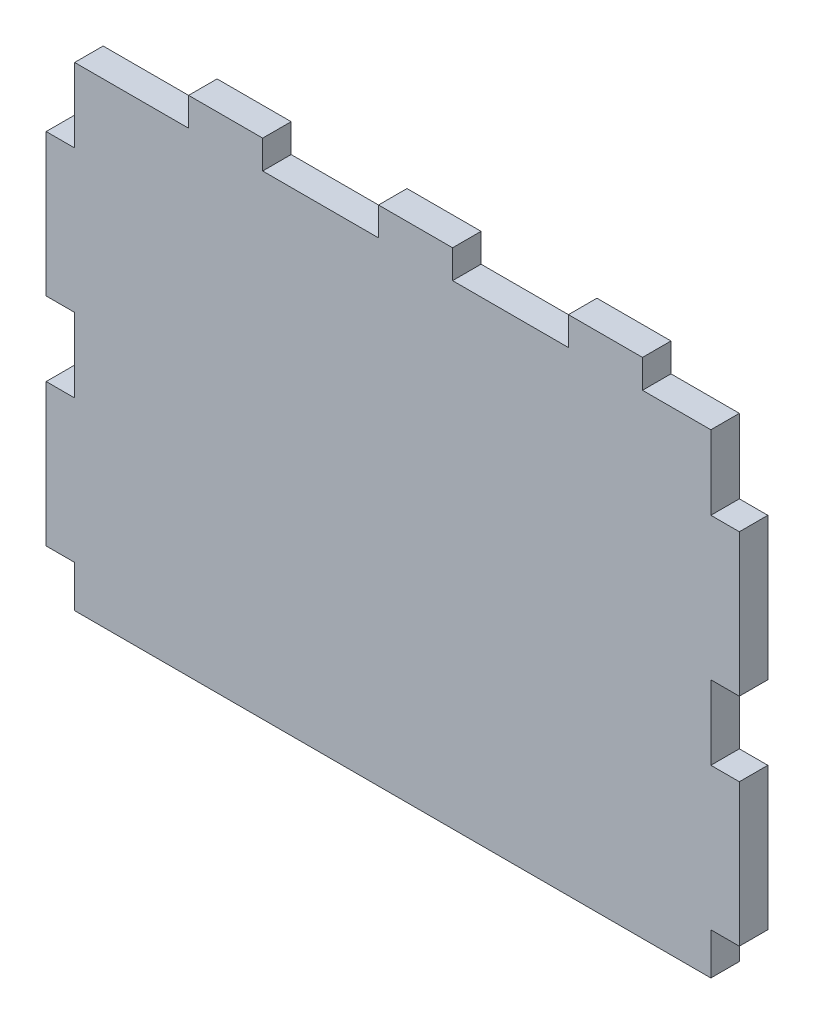
SolidWorks part; units mm, degrees
material "Oak"
ref_plane "Front Plane" through (0, 0, 0) normal (0, 0, 1) x (1, 0, 0)
ref_plane "Top Plane" through (0, 0, 0) normal (0, 1, 0) x (1, 0, 0)
ref_plane "Right Plane" through (0, 0, 0) normal (1, 0, 0) x (0, 0, -1)
sketch "Sketch1" plane through (0, 0, 0) normal (0, 0, 1) x (1, 0, 0)
  line L1 (-40.9935, 16.542) -> (32.0065, 16.542)
  line L2 (-40.9935, 16.542) -> (-40.9935, -33.458)
  line L3 (-40.9935, -33.458) -> (32.0065, -33.458)
  line L4 (32.0065, 16.542) -> (32.0065, -33.458)
  dimension "D1" = 50
  dimension "D2" = 73
extrude "Boss-Extrude1" add sketch "Sketch1" along normal blind 3
sketch "Sketch2" plane through (0, 0, 3) normal (0, 0, 1) x (1, 0, 0)
  line L12 (-40.9935, 16.542) -> (-37.9935, 16.542)
  line L13 (-40.9935, 16.542) -> (-40.9935, 8.742)
  line L14 (-40.9935, 8.742) -> (-37.9935, 8.742)
  line L15 (-37.9935, 16.542) -> (-37.9935, 8.742)
  dimension "D1" = 7.8
  dimension "D2" = 3
extrude "Cut-Extrude1" cut sketch "Sketch2" against normal through all
pattern_linear "LPattern1" count 3 spacing 22.8 along (0, -1, 0) of "Cut-Extrude1"
sketch "Sketch3" plane through (0, 0, 3) normal (0, 0, 1) x (1, 0, 0)
  line L0 (32.0065, 16.542) -> (-37.9935, 16.542) construction
  line L1 (29.0065, 16.542) -> (32.0065, 16.542)
  line L2 (29.0065, 16.542) -> (29.0065, 8.742)
  line L3 (29.0065, 8.742) -> (32.0065, 8.742)
  line L4 (32.0065, 16.542) -> (32.0065, 8.742)
  line L5 (32.0065, -33.458) -> (32.0065, 16.542) construction
  point P8 (30.5065, 16.542)
  dimension "D1" = 7.8
  dimension "D2" = 3
extrude "Cut-Extrude2" cut sketch "Sketch3" against normal through all
pattern_linear "LPattern2" count 4 spacing 22.8 along (0, -1, 0) of "Cut-Extrude2"
sketch "Sketch6" plane through (0, 0, 3) normal (0, 0, 1) x (1, 0, 0)
  line L0 (-37.9935, -33.458) -> (29.0065, -33.458) construction
  line L1 (-40.9935, -14.058) -> (-37.9935, -14.058)
  line L2 (-40.9935, -14.058) -> (-40.9935, -33.458)
  line L3 (-40.9935, -33.458) -> (-37.9935, -33.458)
  line L4 (-37.9935, -14.058) -> (-37.9935, -33.458)
  dimension "D1" = 3
extrude "Cut-Extrude3" cut sketch "Sketch6" against normal blind 10
sketch "Sketch7" plane through (0, 16.542, 0) normal (0, 1, 0) x (1, 0, 0)
  line L0 (29.0065, 0) -> (-37.9935, 0) construction
  line L1 (-25.9935, 0) -> (-18.1935, 0)
  line L2 (-25.9935, 0) -> (-25.9935, -3)
  line L3 (-25.9935, -3) -> (-18.1935, -3)
  line L4 (-18.1935, 0) -> (-18.1935, -3)
  line L5 (29.0065, -3) -> (-37.9935, -3) construction
  line L6 (-37.9935, 0) -> (-37.9935, -3) construction
  dimension "D1" = 12
  dimension "D2" = 7.8
extrude "Boss-Extrude2" add sketch "Sketch7" along normal blind 3
pattern_linear "LPattern3" count 3 spacing 20 along (1, 0, 0) of "Boss-Extrude2"
sketch "Sketch8" plane through (-37.9935, 0, 0) normal (-1, 0, 0) x (0, 0, 1)
  line L0 (0, -33.458) -> (0, -6.258) construction
  line L1 (0, -14.058) -> (3, -14.058)
  line L2 (0, -14.058) -> (0, -29.058)
  line L3 (0, -29.058) -> (3, -29.058)
  line L4 (3, -14.058) -> (3, -29.058)
  line L5 (3, -33.458) -> (3, -6.258) construction
  line L6 (0, -6.258) -> (3, -6.258) construction
  dimension "D1" = 7.8
  dimension "D2" = 15
extrude "Boss-Extrude3" add sketch "Sketch8" along normal blind 3
